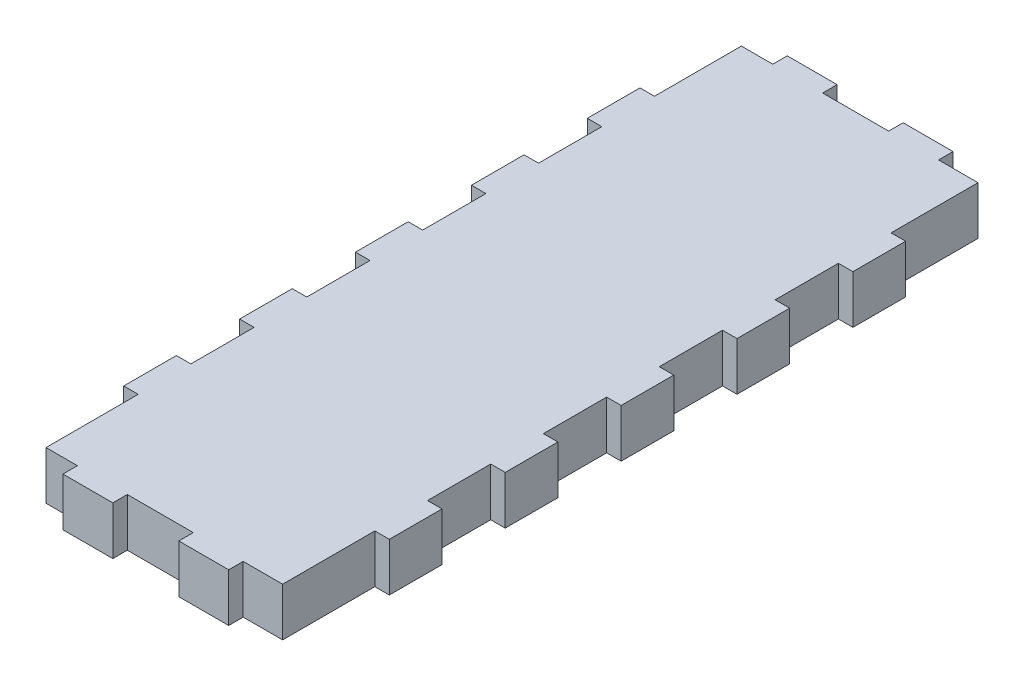
SolidWorks part; units mm, degrees
ref_plane "Front Plane" through (0, 0, 0) normal (0, 0, 1) x (1, 0, 0)
ref_plane "Top Plane" through (0, 0, 0) normal (0, 1, 0) x (1, 0, 0)
ref_plane "Right Plane" through (0, 0, 0) normal (1, 0, 0) x (0, 0, -1)
sketch "Sketch1" plane through (0, 0, 0) normal (0, 1, 0) x (1, 0, 0)
  line L191 (95.0219, 122.7037) -> (108.6871, 122.7037)
  line L192 (84.6871, 125.7037) -> (95.0219, 125.7037)
  line L193 (84.6871, 125.7037) -> (84.6871, 122.7037)
  line L194 (84.6871, -24.2963) -> (95.0219, -24.2963)
  line L195 (95.0219, 125.7037) -> (95.0219, 122.7037)
  line L196 (108.6871, 125.7037) -> (119.0219, 125.7037)
  line L197 (108.6871, 125.7037) -> (108.6871, 122.7037)
  line L198 (108.6871, -24.2963) -> (119.0219, -24.2963)
  line L199 (119.0219, 125.7037) -> (119.0219, 122.7037)
  line L201 (78.1871, -2.201) -> (78.1871, -21.2963)
  line L202 (78.1871, -21.2963) -> (84.6871, -21.2963)
  line L203 (127.1871, -2.201) -> (127.1871, -21.2963)
  line L204 (75.1871, 8.7037) -> (78.1871, 8.7037)
  line L205 (75.1871, 8.7037) -> (75.1871, -2.201)
  line L206 (75.1871, -2.201) -> (78.1871, -2.201)
  line L207 (130.1871, 8.7037) -> (130.1871, -2.201)
  line L209 (78.1871, 21.799) -> (78.1871, 8.7037)
  line L211 (127.1871, 21.799) -> (127.1871, 8.7037)
  line L212 (75.1871, 32.7037) -> (78.1871, 32.7037)
  line L213 (75.1871, 32.7037) -> (75.1871, 21.799)
  line L214 (75.1871, 21.799) -> (78.1871, 21.799)
  line L215 (130.1871, 32.7037) -> (130.1871, 21.799)
  line L217 (78.1871, 45.799) -> (78.1871, 32.7037)
  line L219 (127.1871, 45.799) -> (127.1871, 32.7037)
  line L220 (75.1871, 56.7037) -> (78.1871, 56.7037)
  line L221 (75.1871, 56.7037) -> (75.1871, 45.799)
  line L222 (75.1871, 45.799) -> (78.1871, 45.799)
  line L223 (130.1871, 56.7037) -> (130.1871, 45.799)
  line L225 (78.1871, 69.799) -> (78.1871, 56.7037)
  line L227 (127.1871, 69.799) -> (127.1871, 56.7037)
  line L228 (75.1871, 80.7037) -> (78.1871, 80.7037)
  line L229 (75.1871, 80.7037) -> (75.1871, 69.799)
  line L230 (75.1871, 69.799) -> (78.1871, 69.799)
  line L231 (130.1871, 80.7037) -> (130.1871, 69.799)
  line L233 (78.1871, 80.7037) -> (78.1871, 93.799)
  line L235 (127.1871, 80.7037) -> (127.1871, 93.799)
  line L236 (130.1871, 104.7037) -> (127.1871, 104.7037)
  line L237 (130.1871, 104.7037) -> (130.1871, 93.799)
  line L238 (130.1871, 93.799) -> (127.1871, 93.799)
  line L239 (75.1871, 104.7037) -> (75.1871, 93.799)
  line L240 (78.1871, 122.7037) -> (84.6871, 122.7037)
  line L241 (78.1871, 122.7037) -> (78.1871, 104.7037)
  line L243 (127.1871, 122.7037) -> (127.1871, 104.7037)
  line L244 (84.6871, -21.2963) -> (84.6871, -24.2963)
  line L245 (95.0219, -21.2963) -> (95.0219, -24.2963)
  line L246 (108.6871, -21.2963) -> (108.6871, -24.2963)
  line L247 (119.0219, 122.7037) -> (127.1871, 122.7037)
  line L248 (119.0219, -21.2963) -> (119.0219, -24.2963)
  line L249 (78.1871, 104.7037) -> (75.1871, 104.7037)
  line L250 (127.1871, 69.799) -> (130.1871, 69.799)
  line L251 (78.1871, 93.799) -> (75.1871, 93.799)
  line L252 (127.1871, 80.7037) -> (130.1871, 80.7037)
  line L253 (127.1871, 56.7037) -> (130.1871, 56.7037)
  line L254 (127.1871, 45.799) -> (130.1871, 45.799)
  line L255 (127.1871, 32.7037) -> (130.1871, 32.7037)
  line L256 (127.1871, 21.799) -> (130.1871, 21.799)
  line L257 (127.1871, 8.7037) -> (130.1871, 8.7037)
  line L259 (127.1871, -2.201) -> (130.1871, -2.201)
  line L260 (95.0219, -21.2963) -> (108.6871, -21.2963)
  line L261 (119.0219, -21.2963) -> (127.1871, -21.2963)
extrude "Boss-Extrude1" add sketch "Sketch1" along normal blind 10 separate body
